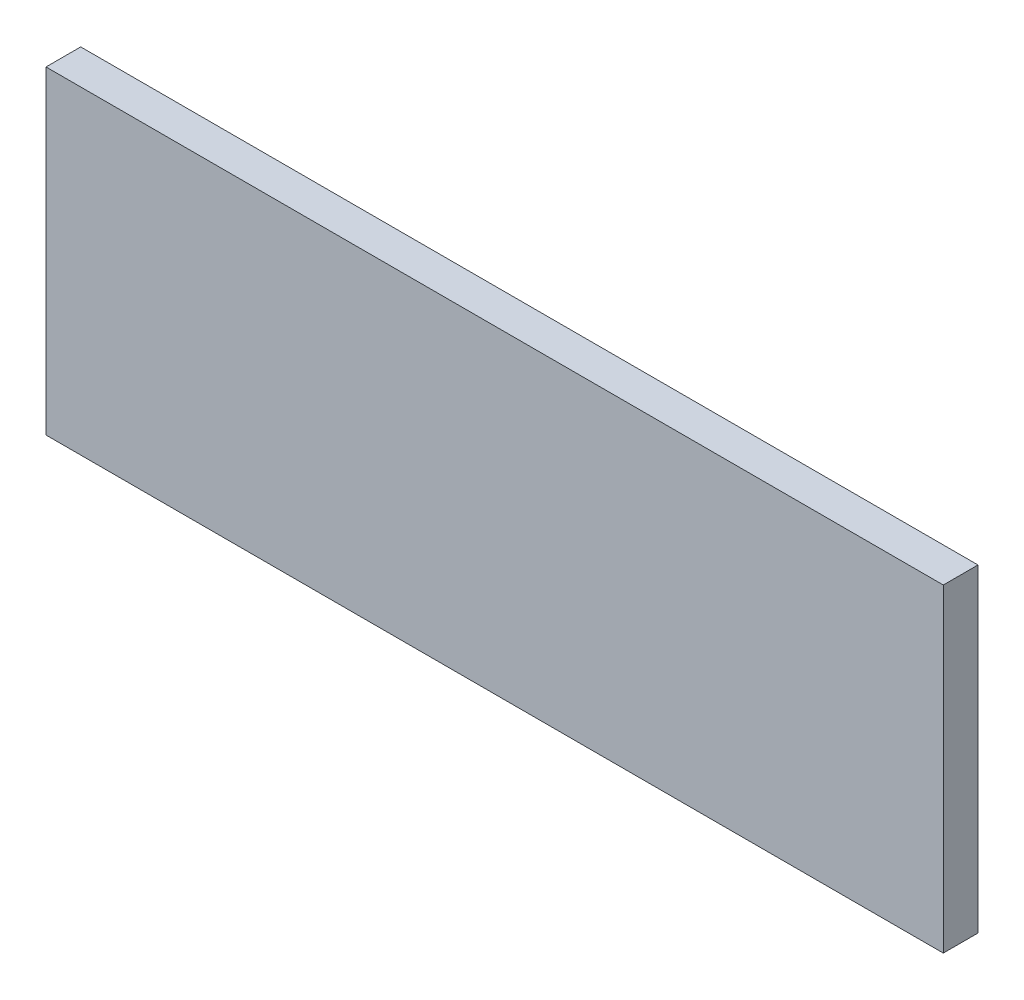
SolidWorks part; units mm, degrees
ref_plane "前视基准面" through (0, 0, 0) normal (0, 0, 1) x (1, 0, 0)
ref_plane "上视基准面" through (0, 0, 0) normal (0, 1, 0) x (1, 0, 0)
ref_plane "右视基准面" through (0, 0, 0) normal (1, 0, 0) x (0, 0, -1)
other "Configuration Table"
sketch "草图1" plane through (0, 0, 0) normal (0, 0, 1) x (1, 0, 0)
  line L1 (0, 0) -> (3000, 0)
  line L2 (0, 0) -> (0, 1000)
  line L3 (0, 1000) -> (3000, 1000)
  line L4 (3000, 0) -> (3000, 1000)
  dimension "D1" = 1000
  dimension "D2" = 3000
extrude "凸台-拉伸2" add sketch "草图1" along normal blind 100 contours L3 L4 L1 L2
sketch "草图3" plane through (0, 0, 100) normal (0, 0, 1) x (1, 0, 0)
  line L0 (0, 1000) -> (0, 1052.41)
  line L1 (0, 1052.41) -> (3000.7384, 1052.41)
  line L2 (3000.7384, 1052.41) -> (3000, 1000)
  line L3 (0, 1052.41) -> (-51.6258, 1052.41)
  line L4 (-51.6258, 1052.41) -> (-51.6258, 0)
  line L5 (-51.6258, 0) -> (0, 0)
  line L6 (3000.7384, 1052.41) -> (3050.5707, 1052.41)
  line L7 (3050.5707, 1052.41) -> (3050.5707, 0)
  line L8 (3050.5707, 0) -> (3000, 0)
  line L9 (-51.6258, 0) -> (-51.6258, -49.7558)
  line L10 (-51.6258, -49.7558) -> (3050.5707, -49.7558)
  line L11 (3050.5707, -49.7558) -> (3050.5707, 0)
  line L12 (0, 1000) -> (3000, 1000)
  line L13 (0, 1000) -> (0, 0)
  line L14 (0, 0) -> (3000, 0)
  line L15 (3000, 0) -> (3000, 1000)
extrude "凸台-拉伸3" add sketch "草图3" against normal blind 120 contours L2 L1 L0 L5 | L4 L5 L2 L0 L3 | L10 L11 L8 L3 L5 L9 | L8 L7 L6 L2 L4
